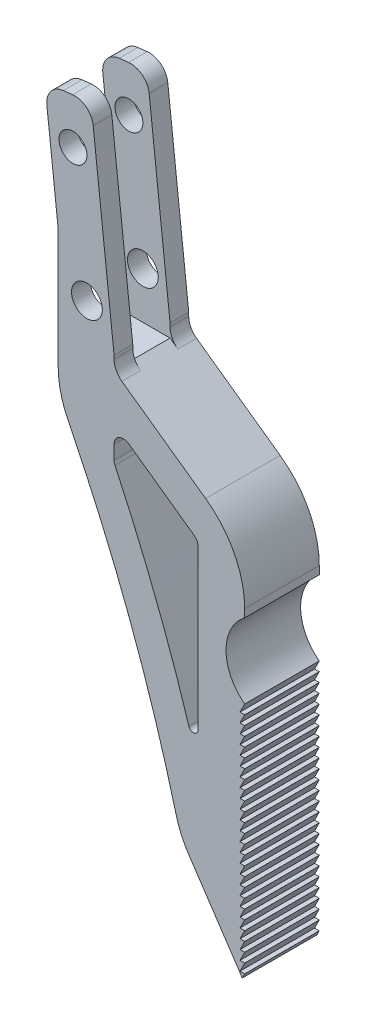
SolidWorks part; units mm, degrees
ref_plane "Front Plane" through (0, 0, 0) normal (0, 0, 1) x (1, 0, 0)
ref_plane "Top Plane" through (0, 0, 0) normal (0, 1, 0) x (1, 0, 0)
ref_plane "Right Plane" through (0, 0, 0) normal (1, 0, 0) x (0, 0, -1)
sketch "Sketch1" plane through (0, 0, 0) normal (0, 0, 1) x (1, 0, 0)
  line L0 (0, 0) -> (-20, 29.9333)
  line L1 (-20, 29.9333) -> (-20, 60.0633)
  line L2 (-20, 60.0633) -> (-21.4356, 72.9838)
  line L3 (-21.4356, 72.9838) -> (-16.4661, 73.5359)
  line L4 (-16.4661, 73.5359) -> (-14.0003, 51.3425)
  line L5 (-14.0003, 51.3425) -> (-14.0003, 49.9425)
  line L6 (-14.0003, 49.9425) -> (0, 39.9562)
  line L7 (0, 39.9562) -> (0, 0)
  dimension "D1" = 20
  dimension "D2" = 36
  dimension "D3" = 30.13
  dimension "D4" = 13
  dimension "D5" = 186.34
  dimension "D6" = 5
  dimension "D7" = 22.33
  dimension "D8" = 1.4
  dimension "D9" = 173.66
  dimension "D10" = 125.5
extrude "Boss-Extrude1" add sketch "Sketch1" along normal mid plane 8
sketch "Sketch2" plane through (0, 0, 0) normal (0, 0, 1) x (1, 0, 0)
  line L1 (-14.0003, 49.9425) -> (-34.0003, 49.9425)
  line L2 (-14.0003, 49.9425) -> (-14.0003, 74.9425)
  line L3 (-14.0003, 74.9425) -> (-34.0003, 74.9425)
  line L4 (-34.0003, 49.9425) -> (-34.0003, 74.9425)
  dimension "D1" = 20
  dimension "D2" = 25
extrude "Cut-Extrude1" cut sketch "Sketch2" against normal mid plane 4
sketch "Sketch3" plane through (0, 0, 4) normal (0, 0, 1) x (1, 0, 0)
  line L0 (0, 0) -> (0, 39.9562) construction
  arc A0 (0, 33.9562) -> (0, 25.9562) centre (3, 29.9562) ccw
  point P3 (0, 0)
  dimension "D1" = 5
  dimension "D2" = 6
  dimension "D3" = 10
extrude "Cut-Extrude2" cut sketch "Sketch3" against normal through all and the other way through all
sketch "Sketch4" plane through (0, 0, 4) normal (0, 0, 1) x (1, 0, 0)
  line L0 (0, 25.9562) -> (-0.5, 24.9562)
  line L1 (-0.5, 24.9562) -> (0, 24.9562)
  line L2 (0, 0) -> (0, 25.9562) construction
  dimension "D1" = 1
  dimension "D2" = 0.5
extrude "Cut-Extrude3" cut sketch "Sketch4" against normal through all and the other way through all
pattern_linear "LPattern1" count 26 spacing 1.0025 along (0, -1, 0) of "Cut-Extrude3"
sketch "Sketch5" plane through (0, 0, 4) normal (0, 0, 1) x (1, 0, 0)
  line L0 (-20, 60.0633) -> (-20, 29.9333) construction
  line L1 (-20, 29.9333) -> (-0.2556, 0.3825) construction
  line L2 (-20, 44.9333) -> (-20, 29.9333)
  line L3 (-20, 29.9333) -> (-6.9333, 10.3769)
  arc A0 (-20, 44.9333) -> (-6.9333, 10.3769) centre (-162.1242, -28.5562) cw
  dimension "D3" = 160
  dimension "D1" = 15
  dimension "D2" = 23.52
extrude "Cut-Extrude4" cut sketch "Sketch5" against normal through all
sketch "Sketch6" plane through (0, 0, 4) normal (0, 0, 1) x (1, 0, 0)
  line L0 (-14.0041, 45.0319) -> (-5, 38.6093)
  line L1 (-5, 38.6093) -> (-5, 17.6719)
  line L2 (0, 33.9562) -> (0, 39.9562) construction
  line L3 (0, 39.9562) -> (-14.0003, 49.9425) construction
  line L4 (-14.0041, 45.0319) -> (-14.0041, 41.3719)
  arc A0 (-14.0041, 41.3719) -> (-5, 17.6719) centre (-158.6012, -27.1239) cw
  dimension "D6" = 160
  dimension "D1" = 4
  dimension "D2" = 5
  dimension "D3" = 3.66
  dimension "D4" = 23.7
  dimension "D5" = 11.06
extrude "Cut-Extrude5" cut sketch "Sketch6" against normal through all
fillet "Fillet1" radius 10 3 edges at (-6.9333, 10.3769, 0) (-20, 44.9333, 0) (0, 39.9562, 0)
fillet "Fillet2" radius 2 6 edges at (-14.0003, 49.9425, -3) (-14.0003, 49.9425, 3) (-16.4661, 73.5359, 3) (-21.4356, 72.9838, 3) (-16.4661, 73.5359, -3) (-21.4356, 72.9838, -3)
fillet "Fillet3" radius 1 3 edges at (-14.0041, 45.0319, 0) (-14.0041, 41.3719, 0) (-5, 38.6093, 0)
fillet "Fillet4" radius 0.5 1 edges at (-5, 17.6719, 0)
sketch "Sketch9" plane through (0, 0, 4) normal (0, 0, 1) x (1, 0, 0)
  line L0 (-18.9509, 73.2598) -> (-16.3869, 50.1833) construction
  line L1 (-18.4539, 73.315) -> (-19.4478, 73.2046) construction
  line L3 (-14.0003, 51.3425) -> (-16.2453, 71.5481) construction
  circle A0 centre (-18.4164, 68.4494) radius 1.5
  circle A1 centre (-16.9157, 54.9425) radius 1.6526
  point P10 (0, 0)
  point P11 (-16.3869, 50.1833)
  dimension "D1" = 3
  dimension "D2" = 3.3052
  dimension "D3" = 4.84
  dimension "D4" = 18.43
extrude "Cut-Extrude6" cut sketch "Sketch9" against normal through all
